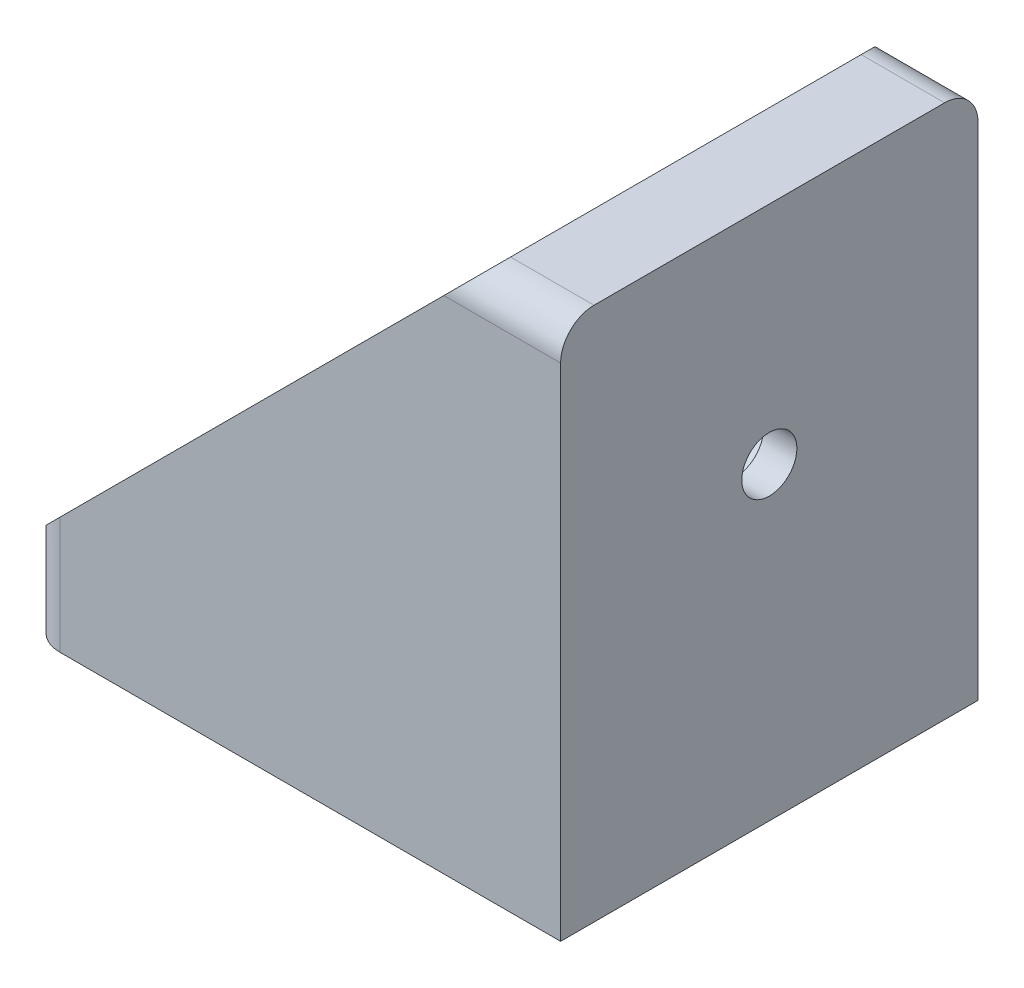
SolidWorks part; units mm, degrees
ref_plane "Спереди" through (0, 0, 0) normal (0, 0, 1) x (1, 0, 0)
ref_plane "Сверху" through (0, 0, 0) normal (0, 1, 0) x (1, 0, 0)
ref_plane "Справа" through (0, 0, 0) normal (1, 0, 0) x (0, 0, -1)
sketch "Эскиз1" plane through (0, 0, 0) normal (0, 0, 1) x (1, 0, 0)
  line L0 (0, 0) -> (-32, 0)
  line L1 (-32, 0) -> (-32, 5)
  line L2 (-32, 5) -> (-5, 5)
  line L3 (-5, 5) -> (-5, 32)
  line L4 (-5, 32) -> (0, 32)
  line L5 (0, 32) -> (0, 0)
  dimension "D1" = 32
  dimension "D2" = 32
  dimension "D3" = 5
  dimension "D4" = 5
extrude "Бобышка-Вытянуть1" add sketch "Эскиз1" along normal blind 25
sketch "Эскиз3" plane through (0, 0, 25) normal (0, 0, 1) x (1, 0, 0)
  line L0 (-32, 5) -> (-5, 32)
rib "Ребро1" sketch "Эскиз3" sketch "Эскиз3" thickness 3 extrusion direction parallel to sketch draft on no parameters "D1"=3
ref_plane "Плоскость4" through (0, 0, 12.5) normal (0, 0, 1) x (1, 0, 0)
mirror "Зеркальное отражение1" about plane through (0, 0, 12.5) normal (0, 0, 1) of "Ребро1"
fillet "Скругление1" radius 2 4 edges at (-2.5, 32, 0) (-2.5, 32, 25) (-32, 2.5, 0) (-32, 2.5, 25)
sketch "Эскиз4" plane through (0, 5, 0) normal (0, 1, 0) x (1, 0, 0)
  line L0 (-5, -22) -> (-32, -3) construction
  line L2 (-15.0359, -12.5) -> (-16.7679, -9.5)
  line L3 (-16.7679, -9.5) -> (-20.2321, -9.5)
  line L4 (-20.2321, -9.5) -> (-21.9641, -12.5)
  line L5 (-21.9641, -12.5) -> (-20.2321, -15.5)
  line L6 (-20.2321, -15.5) -> (-16.7679, -15.5)
  line L7 (-16.7679, -15.5) -> (-15.0359, -12.5)
  circle A0 centre (-18.5, -12.5) radius 3 construction
  dimension "D1" = 6
extrude "Вырез-Вытянуть1" cut sketch "Эскиз4" against normal blind 3
sketch "Эскиз5" plane through (-5, 0, 0) normal (-1, 0, 0) x (0, 0, 1)
  line L0 (3, 5) -> (22, 32) construction
  line L2 (12.5, 15.0359) -> (15.5, 16.7679)
  line L3 (15.5, 16.7679) -> (15.5, 20.2321)
  line L4 (15.5, 20.2321) -> (12.5, 21.9641)
  line L5 (12.5, 21.9641) -> (9.5, 20.2321)
  line L6 (9.5, 20.2321) -> (9.5, 16.7679)
  line L7 (9.5, 16.7679) -> (12.5, 15.0359)
  circle A0 centre (12.5, 18.5) radius 3 construction
  dimension "D1" = 6
extrude "Вырез-Вытянуть2" cut sketch "Эскиз5" against normal blind 3
sketch "Эскиз6" plane through (0, 2, 0) normal (0, 1, 0) x (1, 0, 0)
  circle A0 centre (-18.5, -12.5) radius 3.4641 construction
  circle A1 centre (-18.5, -12.5) radius 1.65
  dimension "D1" = 3.3
sketch "Эскиз7" plane through (-2, 0, 0) normal (-1, 0, 0) x (0, 0, 1)
  circle A0 centre (12.5, 18.5) radius 3.4641 construction
  circle A1 centre (12.5, 18.5) radius 1.65
  dimension "D1" = 3.3
extrude "Вырез-Вытянуть3" cut sketch "Эскиз7" against normal blind 11 contours A1
extrude "Вырез-Вытянуть4" cut sketch "Эскиз6" against normal blind 11 contours A1
